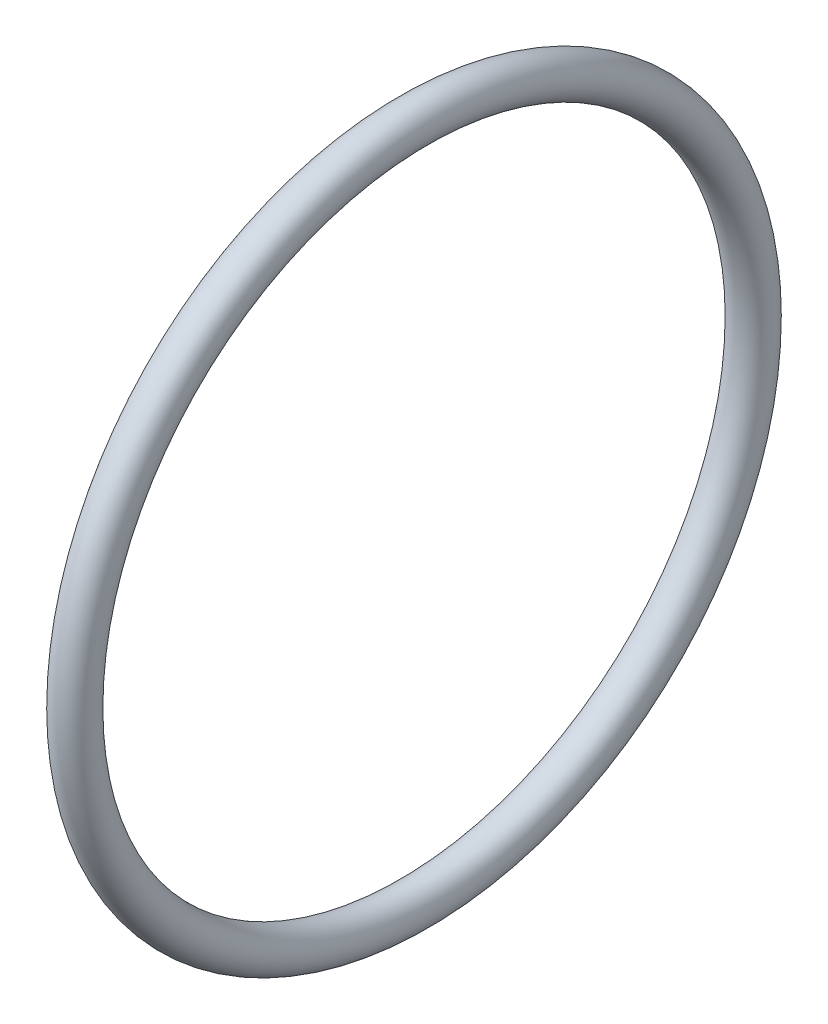
SolidWorks part; units mm, degrees
material "NBR"
ref_plane "前视基准面" through (0, 0, 0) normal (0, 0, 1) x (1, 0, 0)
ref_plane "上视基准面" through (0, 0, 0) normal (0, 1, 0) x (1, 0, 0)
ref_plane "右视基准面" through (0, 0, 0) normal (1, 0, 0) x (0, 0, -1)
sketch "草图1" plane through (0, 0, 0) normal (0, 0, 1) x (1, 0, 0)
  line L0 (0, 0) -> (54.1489, 0) construction
  circle A0 centre (0, 30.135) radius 1.765
  circle A1 centre (0, -30.135) radius 1.765 construction
  dimension "D1" = 56.74
  dimension "D2" = 3.53
revolve "旋转1" add sketch "草图1" angle 360 about L0
ref_plane "基准面1" through (0, 0, 0) normal (1, 0, 0) x (0, 0, -1)
